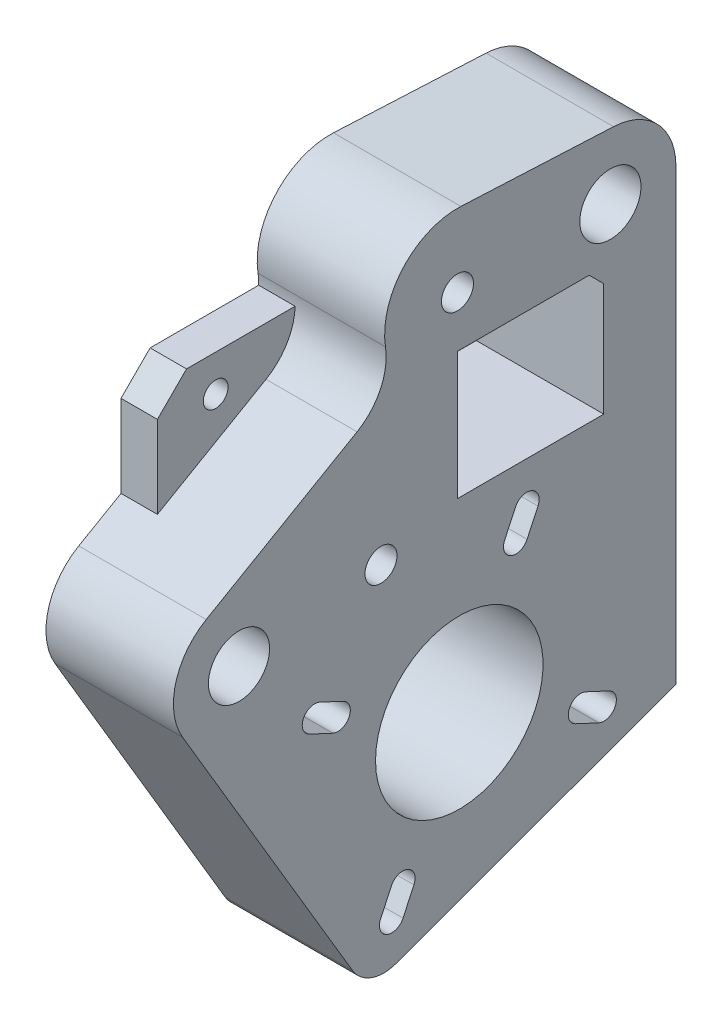
SolidWorks part; units mm, degrees
ref_plane "Front Plane" through (0, 0, 0) normal (0, 0, 1) x (1, 0, 0)
ref_plane "Top Plane" through (0, 0, 0) normal (0, 1, 0) x (1, 0, 0)
ref_plane "Right Plane" through (0, 0, 0) normal (1, 0, 0) x (0, 0, -1)
ref_plane "Plane1" through (0, 0, 0) normal (-1, 0, 0) x (0, -1, 0)
sketch "Sketch1" plane through (0, 0, 0) normal (-1, 0, 0) x (0, -1, 0)
  line L0 (11.2005, 72.3805) -> (-8.7575, 37.8123)
  line L1 (-24.9887, 29.5238) -> (-23.5812, 0)
  line L2 (-23.5812, 0) -> (46.6053, 0)
  line L3 (46.6053, 0) -> (62.0013, 42.3)
  line L4 (62.0013, 42.3) -> (11.2005, 72.3805)
  arc A0 (-8.7575, 37.8123) -> (-24.9887, 29.5238) centre (-15, 30) ccw
extrude "Boss-Extrude1" add sketch "Sketch1" against normal blind 17.5
sketch "Sketch2" plane through (0, 0, 0) normal (-1, 0, 0) x (0, -1, 0)
  line L0 (-8.7575, 37.8123) -> (3.302, 58.7)
  line L1 (3.302, 58.7) -> (-12, 58.7)
  line L2 (-12, 58.7) -> (-12, 39.5394)
  arc A0 (-12, 39.5394) -> (-8.7575, 37.8123) centre (-15, 30) cw
extrude "Boss-Extrude2" add sketch "Sketch2" against normal blind 5
sketch "Sketch3" plane through (0, 0, 0) normal (-1, 0, 0) x (0, 0, 1)
  line L0 (18.9442, -15.9372) -> (20.4384, -19.1415)
  line L1 (23.5198, -17.7046) -> (22.0256, -14.5003)
  arc A0 (20.4384, -19.1415) -> (23.5198, -17.7046) centre (21.9791, -18.423) ccw
  arc A1 (22.0256, -14.5003) -> (18.9442, -15.9372) centre (20.4849, -15.2188) ccw
extrude "Cut-Extrude1" cut sketch "Sketch3" against normal through all
sketch "Sketch4" plane through (0, 0, 0) normal (-1, 0, 0) x (0, 0, 1)
  line L0 (48.8969, -24.2807) -> (45.6927, -25.7748)
  line L1 (47.1296, -28.8563) -> (50.3338, -27.3621)
  arc A0 (50.3338, -27.3621) -> (48.8969, -24.2807) centre (49.6154, -25.8214) ccw
  arc A1 (45.6927, -25.7748) -> (47.1296, -28.8563) centre (46.4111, -27.3156) ccw
extrude "Cut-Extrude2" cut sketch "Sketch4" against normal through all
sketch "Sketch5" plane through (0, 0, 0) normal (-1, 0, 0) x (0, 0, 1)
  line L0 (35.9779, -52.466) -> (37.472, -55.6703)
  line L1 (40.5535, -54.2334) -> (39.0593, -51.0291)
  arc A0 (37.472, -55.6703) -> (40.5535, -54.2334) centre (39.0128, -54.9518) ccw
  arc A1 (39.0593, -51.0291) -> (35.9779, -52.466) centre (37.5186, -51.7476) ccw
extrude "Cut-Extrude3" cut sketch "Sketch5" against normal through all
sketch "Sketch6" plane through (0, 0, 0) normal (-1, 0, 0) x (0, 0, 1)
  line L0 (10.6007, -45.8899) -> (13.805, -44.3958)
  line L1 (12.3681, -41.3143) -> (9.1638, -42.8085)
  arc A0 (13.805, -44.3958) -> (12.3681, -41.3143) centre (13.0866, -42.855) ccw
  arc A1 (9.1638, -42.8085) -> (10.6007, -45.8899) centre (9.8823, -44.3492) ccw
extrude "Cut-Extrude4" cut sketch "Sketch6" against normal through all
sketch "Sketch7" plane through (17.5, 0, 0) normal (1, 0, 0) x (0, 0, -1)
  line L0 (-30, 7.9961) -> (-30, -9.5217)
  line L1 (-30, -9.5217) -> (-9.9147, -9.5217)
  line L3 (-9.9147, -9.5217) -> (-9.9147, 7.9961)
  line L4 (-9.9147, 7.9961) -> (-30, 7.9961)
  dimension "D1" = 17.5178
extrude "Cut-Extrude5" cut sketch "Sketch7" against normal through all
hole_wizard "Hole1" positions "Sketch9" profile "Sketch8" legacy
sketch "Sketch9" plane through (5, 0, 0) normal (1, 0, 0) x (0, 0, -1)
  point P0 (-50.7, 7)
sketch "Sketch8" plane through (5, 7, 50.7) normal (0, 1, 0) x (0, 0, -1)
  line L0 (0, 0) -> (0, 5)
  line L1 (0, 5) -> (1.7, 5)
  line L2 (1.7, 5) -> (1.7, 0)
  line L3 (1.7, 0) -> (0, 0)
  line L4 (0, 110) -> (0, -10) construction
  dimension "Diameter" = 3.4
  dimension "Depth" = 5
hole_wizard "Hole2" positions "Sketch11" profile "Sketch10" legacy
sketch "Sketch11" plane through (0, 0, 0) normal (-1, 0, 0) x (0, 0, 1)
  point P0 (9, 15)
sketch "Sketch10" plane through (0, 15, 9) normal (0, 1, 0) x (0, 0, 1)
  line L0 (0, 0) -> (0, 17.5)
  line L1 (0, 17.5) -> (4.2, 17.5)
  line L2 (4.2, 17.5) -> (4.2, 0)
  line L3 (4.2, 0) -> (0, 0)
  line L4 (0, 110) -> (0, -10) construction
  dimension "Diameter" = 8.4
  dimension "Depth" = 17.5
hole_wizard "Hole3" positions "Sketch13" profile "Sketch12" legacy
sketch "Sketch13" plane through (0, 0, 0) normal (-1, 0, 0) x (0, 0, 1)
  point P0 (40.5, -12.1507)
sketch "Sketch12" plane through (0, -12.1507, 40.5) normal (0, 1, 0) x (0, 0, 1)
  line L0 (0, 0) -> (0, 17.5)
  line L1 (0, 17.5) -> (2.2, 17.5)
  line L2 (2.2, 17.5) -> (2.2, 0)
  line L3 (2.2, 0) -> (0, 0)
  line L4 (0, 110) -> (0, -10) construction
  dimension "Diameter" = 4.4
  dimension "Depth" = 17.5
hole_wizard "Hole4" positions "Sketch15" profile "Sketch14" legacy
sketch "Sketch15" plane through (0, 0, 0) normal (-1, 0, 0) x (0, 0, 1)
  point P0 (29.7488, -35.0853)
sketch "Sketch14" plane through (0, -35.0853, 29.7488) normal (0, 1, 0) x (0, 0, 1)
  line L0 (0, 0) -> (0, 17.5)
  line L1 (0, 17.5) -> (11.5, 17.5)
  line L2 (11.5, 17.5) -> (11.5, 0)
  line L3 (11.5, 0) -> (0, 0)
  line L4 (0, 110) -> (0, -10) construction
  dimension "Diameter" = 23
  dimension "Depth" = 17.5
hole_wizard "Hole5" positions "Sketch17" profile "Sketch16" legacy
sketch "Sketch17" plane through (0, 0, 0) normal (-1, 0, 0) x (0, 0, 1)
  point P0 (60, -14.4449)
sketch "Sketch16" plane through (0, -14.4449, 60) normal (0, 1, 0) x (0, 0, 1)
  line L0 (0, 0) -> (0, 17.5)
  line L1 (0, 17.5) -> (4.2, 17.5)
  line L2 (4.2, 17.5) -> (4.2, 0)
  line L3 (4.2, 0) -> (0, 0)
  line L4 (0, 110) -> (0, -10) construction
  dimension "Diameter" = 8.4
  dimension "Depth" = 17.5
hole_wizard "Hole6" positions "Sketch19" profile "Sketch18" legacy
sketch "Sketch19" plane through (0, 0, 0) normal (-1, 0, 0) x (0, 0, 1)
  point P0 (30, 15)
sketch "Sketch18" plane through (0, 15, 30) normal (0, 1, 0) x (0, 0, 1)
  line L0 (0, 0) -> (0, 17.5)
  line L1 (0, 17.5) -> (2.2, 17.5)
  line L2 (2.2, 17.5) -> (2.2, 0)
  line L3 (2.2, 0) -> (0, 0)
  line L4 (0, 110) -> (0, -10) construction
  dimension "Diameter" = 4.4
  dimension "Depth" = 17.5
fillet "Fillet1" radius 8 1 edges at (11.25, 8.7575, 37.8123)
chamfer "Chamfer3" distance 4 angle 45 1 edges at (2.5, 12, 58.7)
chamfer "Chamfer4" distance 2 angle 45 1 edges at (8.75, 7.9961, 9.9147)
fillet "Fillet2" radius 5 1 edges at (8.75, -62.0013, 42.3)
fillet "Fillet3" radius 9 1 edges at (8.75, -11.2005, 72.3805)
fillet "Fillet4" radius 9 1 edges at (8.75, 23.5812, 0)
